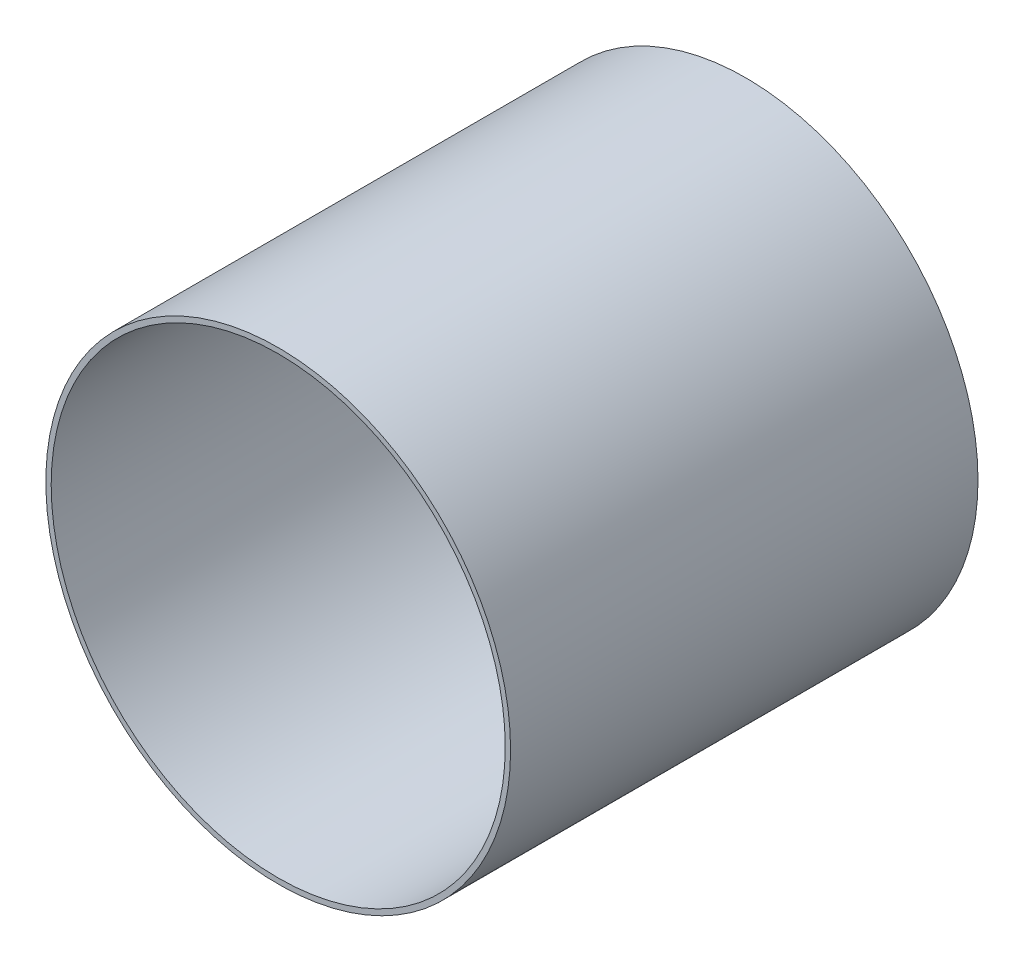
SolidWorks part; units mm, degrees
ref_plane "Front Plane" through (0, 0, 0) normal (0, 0, 1) x (1, 0, 0)
ref_plane "Top Plane" through (0, 0, 0) normal (0, 1, 0) x (1, 0, 0)
ref_plane "Right Plane" through (0, 0, 0) normal (1, 0, 0) x (0, 0, -1)
sketch "Sketch1" plane through (0, 0, 0) normal (0, 0, 1) x (1, 0, 0)
  circle A0 centre (0, 0) radius 42.5
  circle A1 centre (0, 0) radius 43.5
  dimension "D1" = 1
extrude "Boss-Extrude1" add sketch "Sketch1" along normal blind 87.5
